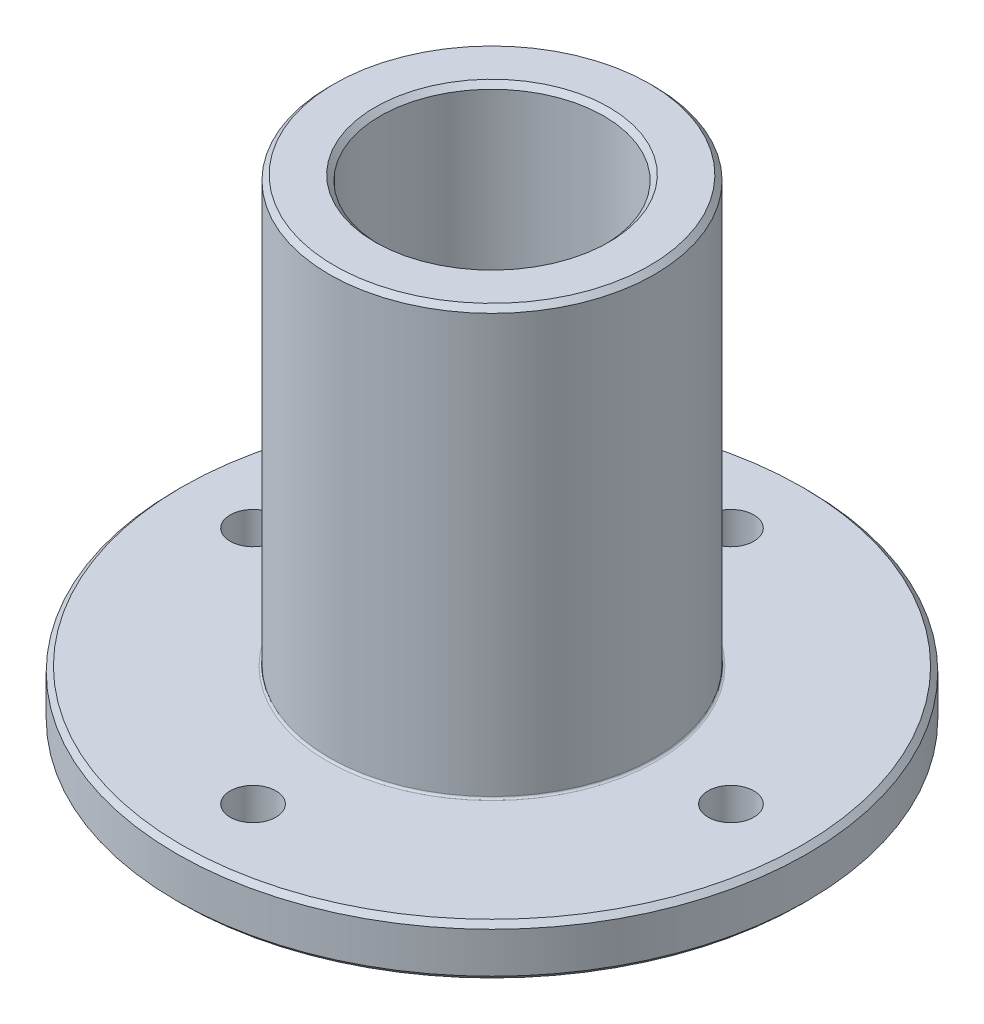
SolidWorks part; units mm, degrees
ref_plane "Front" through (0, 0, 0) normal (0, 0, 1) x (1, 0, 0)
ref_plane "Top" through (0, 0, 0) normal (0, 1, 0) x (1, 0, 0)
ref_plane "Right" through (0, 0, 0) normal (1, 0, 0) x (0, 0, -1)
sketch "Sketch1" plane through (0, 0, 0) normal (0, 0, 1) x (1, 0, 0)
  line L0 (0, 9.4882) -> (0, -13.8189) construction
  line L1 (9, 0) -> (31, 0)
  line L2 (31, 0) -> (31, 5)
  line L3 (31, 5) -> (16, 5)
  line L4 (16, 5) -> (16, 46.85)
  line L5 (16, 46.85) -> (11, 46.85)
  line L6 (11, 46.85) -> (11, 8.85)
  line L7 (11, 8.85) -> (9, 8.85)
  line L8 (9, 8.85) -> (9, 0)
  line L10 (-8, 14.85) -> (8, 14.85) construction
  line L11 (-5, 43.85) -> (5, 43.85) construction
  dimension "D1" = 5
  dimension "D2" = 5
  dimension "D3" = 2
  dimension "D4" = 9
  dimension "D5" = 15
  dimension "D6" = 3
  dimension "D7" = 6
revolve "Revolve1" add sketch "Sketch1" angle 360 about L0
hole_wizard "M4 Clearance Hole1" positions "Sketch2" profile "Sketch3" hole size "M4" standard "ISO"
sketch "Sketch2" plane through (0, 5, 0) normal (0, 1, 0) x (1, 0, 0)
  circle A0 centre (0, 0) radius 23.5 construction
  point P0 (23.5, 0)
  point P7 (0, 23.5)
  point P9 (0, -23.5)
  point P11 (-23.5, 0)
  dimension "D1" = 47
sketch "Sketch3" plane through (23.5, 5, 0) normal (1, 0, 0) x (0, 0, 1)
  line L0 (0, 0) -> (0, 11.3519)
  line L1 (0, 11.3519) -> (2.25, 10)
  line L2 (2.25, 10) -> (2.25, 0)
  line L5 (2.25, 0) -> (0, 0)
  line L10 (0, 11.3519) -> (-2.25, 10) construction
  line L11 (0, -6.35) -> (0, 107.95) construction
  dimension "Hole Dia." = 4.5
  dimension "Hole Depth" = 10
  dimension "Drill Angle" = 118
ref_plane "Plane1" through (0, 9.4882, 0) normal (-1, 0, 0) x (0, 0, 1)
sketch "Sketch5" plane through (0, 9.4882, 0) normal (-1, 0, 0) x (0, 0, 1)
  line L0 (11.39, 5.3618) -> (9.9, 5.3618)
  line L1 (9.9, 5.3618) -> (9.9, 6.4618)
  line L2 (9.9, 6.4618) -> (11.39, 6.4618)
  line L3 (11.5, 6.3518) -> (11.5, 5.4718)
  line L4 (0, -50) -> (0, 50) construction
  line L6 (11, -0.6382) -> (-11, -0.6382) construction
  arc A0 (11.5, 5.4718) -> (11.39, 5.3618) centre (11.39, 5.4718) cw
  arc A1 (11.5, 6.3518) -> (11.39, 6.4618) centre (11.39, 6.3518) ccw
  dimension "D1" = 0.11
  dimension "D2" = 0.11
  dimension "D3" = 1.1
  dimension "D4" = 1.49
  dimension "D5" = 9.9
  dimension "D6" = 6
revolve "Groove for BS 3673 P4 - B022M, Internal Circlip1" cut sketch "Sketch5"
fillet "Fillet1" radius 0.2 2 edges at (0, 5, 16) (0, 8.85, 11)
chamfer "Chamfer1" distance 0.5 angle 45 6 edges at (0, 0, 31) (0, 5, 31) (0, 46.85, 16) (0, 0, 9) (0, 46.85, 11) (0, 8.85, 9)
